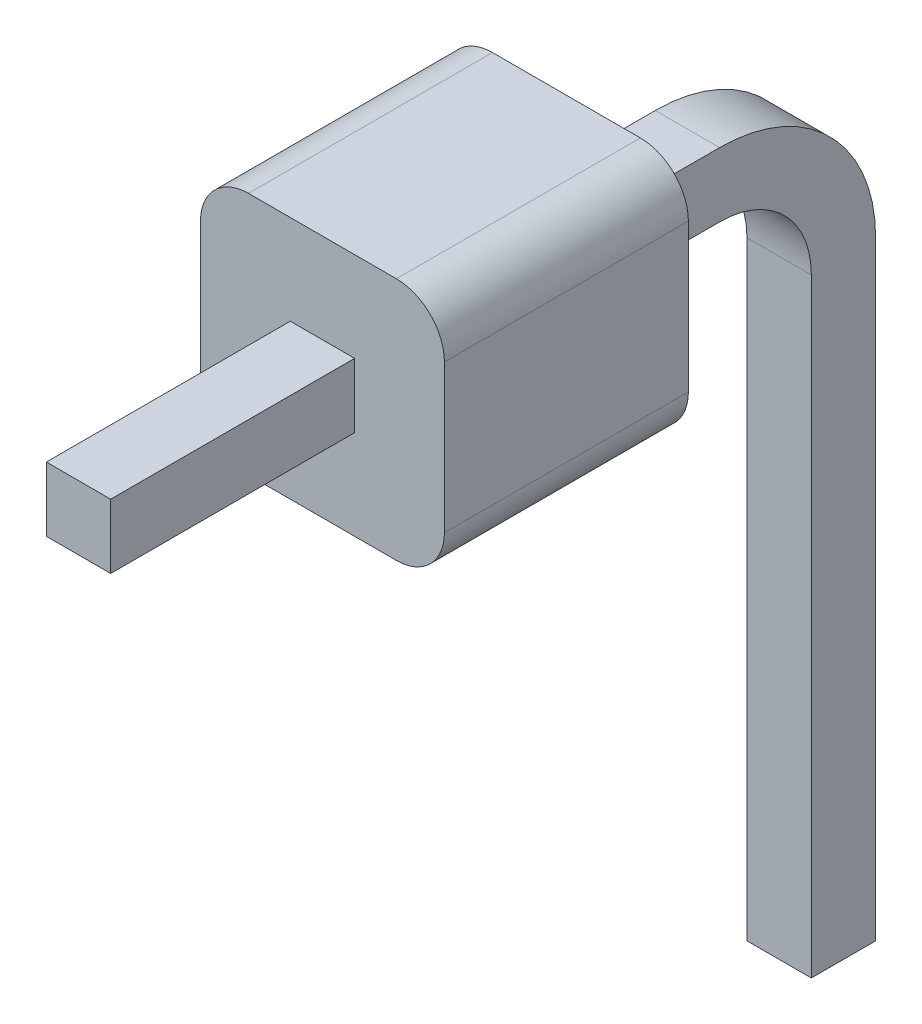
SolidWorks part; units mm, degrees
ref_plane "前视基准面" through (0, 0, 0) normal (0, 0, 1) x (1, 0, 0)
ref_plane "上视基准面" through (0, 0, 0) normal (0, 1, 0) x (1, 0, 0)
ref_plane "右视基准面" through (0, 0, 0) normal (1, 0, 0) x (0, 0, -1)
sketch "草图1" plane through (0, 0, 0) normal (0, 0, 1) x (1, 0, 0)
  line L0 (0, 5.3599) -> (0, -8.0108) construction
  line L1 (-1.27, -0.0191) -> (1.27, -0.0191)
  line L2 (-1.27, -0.0191) -> (-1.27, -2.5591)
  line L3 (-1.27, -2.5591) -> (1.27, -2.5591)
  line L4 (1.27, -0.0191) -> (1.27, -2.5591)
  dimension "D1" = 2.54
  dimension "D2" = 2.54
extrude "拉伸1" add sketch "草图1" along normal blind 2.54
ref_plane "基准面1" through (0, 0, 5.08) normal (0, 0, -1) x (-1, 0, 0)
sketch "草图2" plane through (0, 0, 5.08) normal (0, 0, -1) x (-1, 0, 0)
  line L0 (-1.27, -1.2891) -> (1.27, -1.2891) construction
  line L1 (-1.27, -2.5591) -> (-1.27, -0.0191) construction
  line L2 (1.27, -0.0191) -> (1.27, -2.5591) construction
  line L3 (0, 1.9407) -> (0, -4.2425) construction
  line L5 (-0.335, -0.9541) -> (0.335, -0.9541)
  line L6 (-0.335, -0.9541) -> (-0.335, -1.6241)
  line L7 (-0.335, -1.6241) -> (0.335, -1.6241)
  line L8 (0.335, -0.9541) -> (0.335, -1.6241)
  dimension "D1" = 0.67
  dimension "D2" = 0.67
sketch "草图3" plane through (0, 0, 0) normal (1, 0, 0) x (0, 0, -1)
  line L0 (1.26, -1.2991) -> (-5.08, -1.2991)
  line L3 (2.54, -2.5791) -> (2.54, -8.9191)
  line L8 (-2.54, -0.0191) -> (0, -0.0191) construction
  line L9 (0, -2.5591) -> (0, -0.0191) construction
  arc A0 (2.54, -2.5791) -> (1.26, -1.2991) centre (1.26, -2.5791) ccw
  point P11 (2.54, -1.2991)
  dimension "D5" = 1.28
  dimension "D1" = 5.08
  dimension "D2" = 2.54
  dimension "D3" = 7.62
  dimension "D4" = 1.28
sweep "扫描1" add profiles "草图2" path "草图3"
fillet "圆角1" radius 0.5 4 edges at (1.27, -0.0191, 1.27) (1.27, -2.5591, 1.27) (-1.27, -2.5591, 1.27) (-1.27, -0.0191, 1.27)
